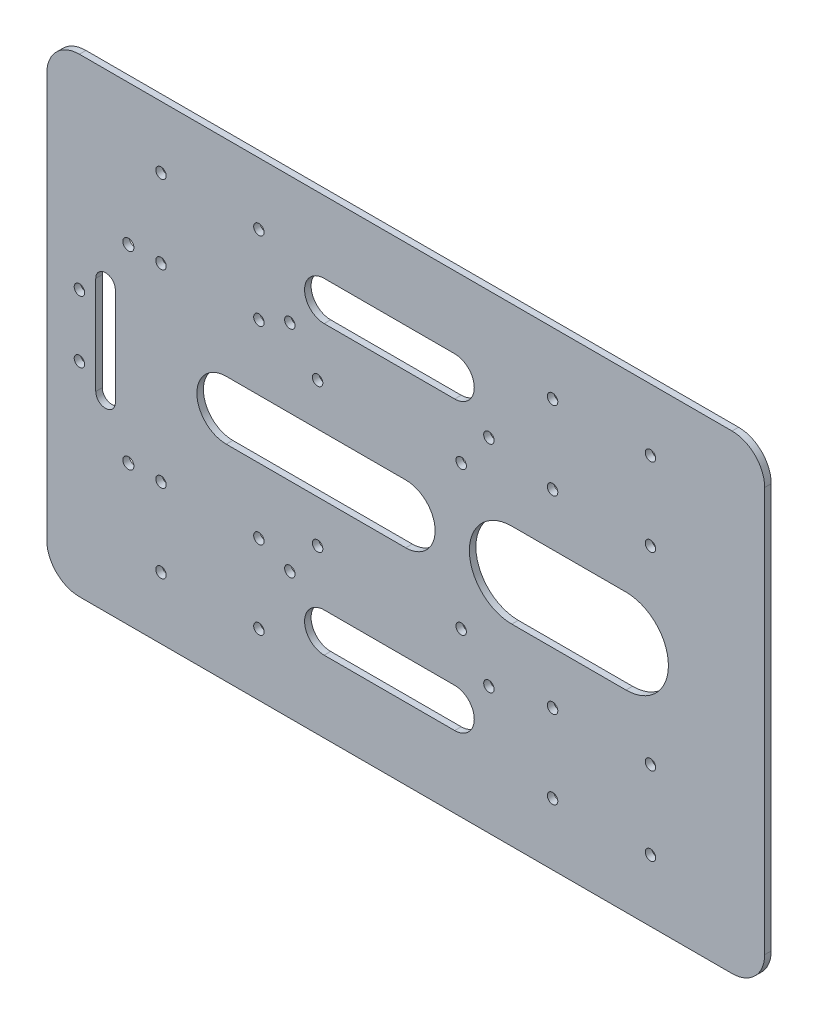
SolidWorks part; units mm, degrees
ref_plane "前视基准面" through (0, 0, 0) normal (0, 0, 1) x (1, 0, 0)
ref_plane "上视基准面" through (0, 0, 0) normal (0, 1, 0) x (1, 0, 0)
ref_plane "右视基准面" through (0, 0, 0) normal (1, 0, 0) x (0, 0, -1)
sketch "草图1" plane through (0, 0, 0) normal (0, 0, 1) x (1, 0, 0)
  line L1 (140, 20.5) -> (-20, 20.5)
  line L2 (140, 20.5) -> (140, -103.5)
  line L3 (140, -103.5) -> (-20, -103.5)
  line L4 (-20, 20.5) -> (-20, -103.5)
  line L5 (-50, -113.5) -> (170, -113.5)
  line L6 (-50, -113.5) -> (-50, 30.5)
  line L7 (-50, 30.5) -> (170, 30.5)
  line L8 (170, -113.5) -> (170, 30.5)
  circle A0 centre (135, 11.5) radius 1.6
  circle A1 centre (135, -12.5) radius 1.6
  circle A2 centre (105, 11.5) radius 1.6
  circle A3 centre (105, -12.5) radius 1.6
  circle A4 centre (135, -70.5) radius 1.6
  circle A5 centre (135, -94.5) radius 1.6
  circle A6 centre (105, -70.5) radius 1.6
  circle A7 centre (105, -94.5) radius 1.6
  circle A8 centre (15, 11.5) radius 1.6
  circle A9 centre (-15, 11.5) radius 1.6
  circle A10 centre (15, -12.5) radius 1.6
  circle A11 centre (-15, -12.5) radius 1.6
  circle A12 centre (15, -70.5) radius 1.6
  circle A13 centre (-15, -70.5) radius 1.6
  circle A14 centre (15, -94.5) radius 1.6
  circle A15 centre (-15, -94.5) radius 1.6
  circle A16 centre (24.4873, -8.4999) radius 1.6002
  circle A17 centre (85.4874, -8.4999) radius 1.6002
  circle A18 centre (24.4873, -74.5001) radius 1.6
  circle A19 centre (85.4874, -74.5001) radius 1.6002
  circle A20 centre (76.9873, -19.5001) radius 1.6
  circle A21 centre (76.9873, -63.5001) radius 1.6
  circle A22 centre (32.9873, -63.5001) radius 1.6
  circle A23 centre (32.9873, -19.5001) radius 1.6
  dimension "D1" = 10
  dimension "D5" = 3.2
  dimension "D6" = 3.2
  dimension "D7" = 3.2
  dimension "D8" = 3.2
  dimension "D9" = 3.2
  dimension "D2" = 10
  dimension "D3" = 30
  dimension "D4" = 30
extrude "凸台-拉伸1" add sketch "草图1" along normal blind 2 contours L1 L4 L3 L2 A15 A14 A13 A12 A11 A10 A9 A8 A7 A6 A5 A4 A3 A2 A1 A0 | L5 L8 L7 L6 L4 L1 L2 L3
sketch "草图4" plane through (0, 0, 2) normal (0, 0, 1) x (1, 0, 0)
  line L0 (-50, -41.5) -> (170, -41.5) construction
  line L1 (-50, -113.5) -> (-50, 30.5) construction
  line L2 (170, -113.5) -> (170, 30.5) construction
  line L3 (92.5, -41.5) -> (127.5, -41.5) construction
  line L4 (92.5, -28.5) -> (127.5, -28.5)
  line L5 (92.5, -54.5) -> (127.5, -54.5)
  arc A0 (92.5, -28.5) -> (92.5, -54.5) centre (92.5, -41.5) ccw
  arc A1 (127.5, -54.5) -> (127.5, -28.5) centre (127.5, -41.5) ccw
  point P8 (110, -41.5)
  dimension "D2" = 35
  dimension "D3" = 13
  dimension "D1" = 60
extrude "切除-拉伸1" cut sketch "草图4" against normal blind 10
fillet "圆角1" radius 10 4 edges at (-50, 30.5, 1) (170, 30.5, 1) (170, -113.5, 1) (-50, -113.5, 1)
sketch "草图5" plane through (0, 0, 2) normal (0, 0, 1) x (1, 0, 0)
  line L0 (170, -41.5) -> (-50, -41.5) construction
  line L1 (170, -103.5) -> (170, 20.5) construction
  line L2 (-50, -103.5) -> (-50, 20.5) construction
  line L3 (5, -41.5) -> (60, -41.5) construction
  line L4 (5, -32.5) -> (60, -32.5)
  line L5 (5, -50.5) -> (60, -50.5)
  arc A1 (5, -32.5) -> (5, -50.5) centre (5, -41.5) ccw
  arc A2 (60, -50.5) -> (60, -32.5) centre (60, -41.5) ccw
  point P8 (32.5, -41.5)
  dimension "D1" = 55
  dimension "D2" = 9
extrude "切除-拉伸2" cut sketch "草图5" against normal blind 10
sketch "草图6" plane through (0, 0, 2) normal (0, 0, 1) x (1, 0, 0)
  line L0 (35, 2.5) -> (75, 2.5) construction
  line L1 (35, 8.5) -> (75, 8.5)
  line L2 (35, -3.5) -> (75, -3.5)
  line L3 (-40, 30.5) -> (160, 30.5) construction
  line L4 (-50, -103.5) -> (-50, 20.5) construction
  line L5 (140.5, -41.5) -> (-50, -41.5) construction
  line L6 (35, -85.5) -> (75, -85.5) construction
  line L9 (35, -91.5) -> (75, -91.5)
  line L10 (35, -79.5) -> (75, -79.5)
  arc A0 (35, 8.5) -> (35, -3.5) centre (35, 2.5) ccw
  arc A1 (75, -3.5) -> (75, 8.5) centre (75, 2.5) ccw
  arc A2 (127.5, -54.5) -> (127.5, -28.5) centre (127.5, -41.5) ccw construction
  arc A5 (35, -91.5) -> (35, -79.5) centre (35, -85.5) cw
  arc A6 (75, -79.5) -> (75, -91.5) centre (75, -85.5) cw
  point P3 (55, 2.5)
  point P19 (55, -85.5)
  dimension "D3" = 6
  dimension "D1" = 40
  dimension "D2" = 22
  dimension "D4" = 105
extrude "切除-拉伸3" cut sketch "草图6" against normal blind 10
sketch "草图8" plane through (0, 0, 2) normal (0, 0, 1) x (1, 0, 0)
  line L0 (170, -41.5) -> (-50, -41.5) construction
  line L1 (170, -103.5) -> (170, 20.5) construction
  line L2 (-50, -103.5) -> (-50, 20.5) construction
  line L3 (-32, -26.5) -> (-32, -56.5) construction
  line L4 (-29, -26.5) -> (-29, -56.5)
  line L5 (-35, -26.5) -> (-35, -56.5)
  circle A0 centre (-40, -32) radius 1.6
  circle A1 centre (-40, -51) radius 1.6
  arc A2 (-29, -26.5) -> (-35, -26.5) centre (-32, -26.5) ccw
  arc A3 (-35, -56.5) -> (-29, -56.5) centre (-32, -56.5) ccw
  point P12 (-32, -41.5)
  dimension "D1" = 3.2
  dimension "D2" = 19
  dimension "D3" = 10
  dimension "D4" = 6
  dimension "D5" = 30
  dimension "D6" = 18
extrude "切除-拉伸4" cut sketch "草图8" against normal blind 10
sketch "草图9" plane through (0, 0, 2) normal (0, 0, 1) x (1, 0, 0)
  circle A0 centre (-25, -70.5) radius 1.7
  circle A1 centre (-25, -12.5) radius 1.7
extrude "切除-拉伸5" cut sketch "草图9" against normal blind 10
